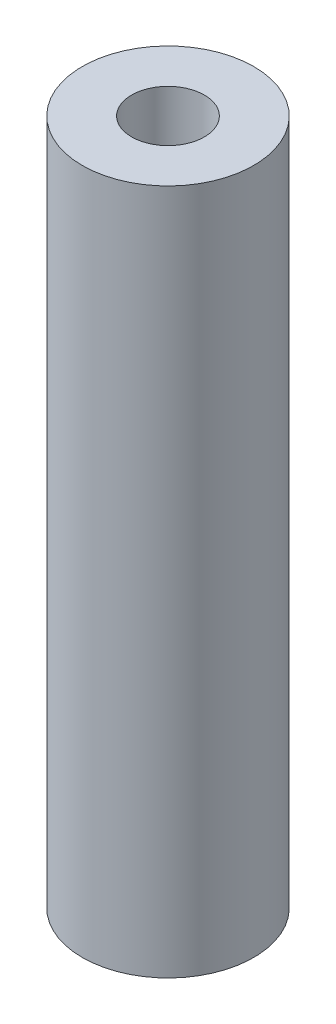
SolidWorks part; units mm, degrees
material "6061-T6 (SS)"
ref_plane "Front Plane" through (0, 0, 0) normal (0, 0, 1) x (1, 0, 0)
ref_plane "Top Plane" through (0, 0, 0) normal (0, 1, 0) x (1, 0, 0)
ref_plane "Right Plane" through (0, 0, 0) normal (1, 0, 0) x (0, 0, -1)
sketch "Sketch1" plane through (0, 0, 0) normal (0, 1, 0) x (1, 0, 0)
  circle A0 centre (0, 0) radius 2.0193
  circle A1 centre (0, 0) radius 4.7625
  dimension "D1" = 9.525
  dimension "D2" = 4.0386
extrude "Boss-Extrude1" add sketch "Sketch1" along normal blind 38.1
